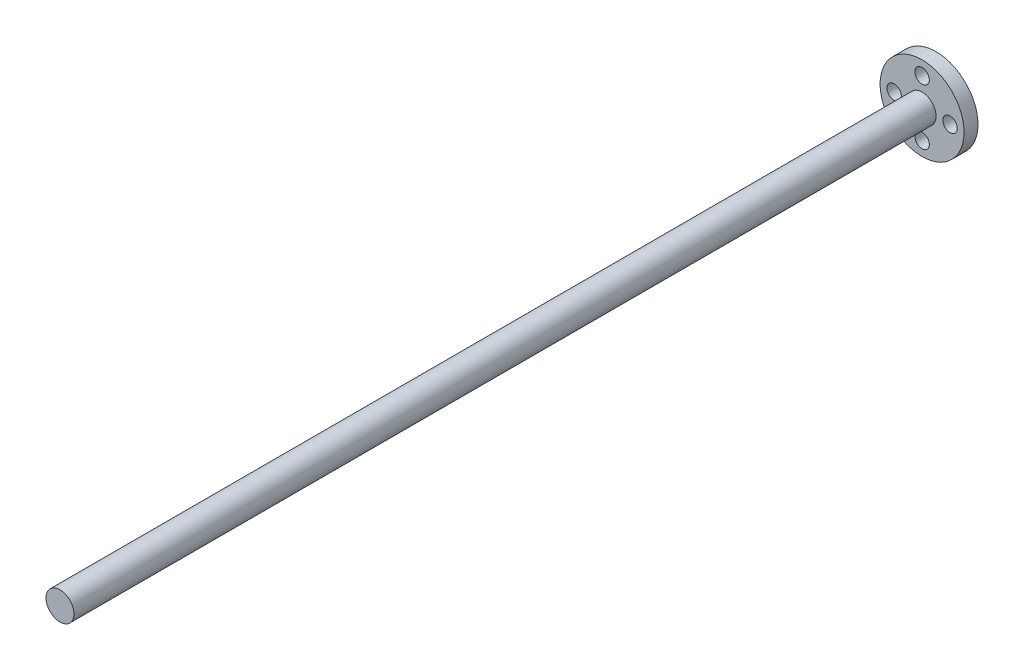
SolidWorks part; units mm, degrees
ref_plane "Front Plane" through (0, 0, 0) normal (0, 0, 1) x (1, 0, 0)
ref_plane "Top Plane" through (0, 0, 0) normal (0, 1, 0) x (1, 0, 0)
ref_plane "Right Plane" through (0, 0, 0) normal (1, 0, 0) x (0, 0, -1)
sketch "Sketch1" plane through (0, 0, 0) normal (0, 0, 1) x (1, 0, 0)
  circle A0 centre (0, 0) radius 9
  circle A1 centre (0, 0) radius 6 construction
  circle A2 centre (-6, 0) radius 1.55
  circle A3 centre (0, 6) radius 1.55
  circle A4 centre (6, 0) radius 1.55
  circle A5 centre (0, -6) radius 1.55
  point P15 (0, 0)
  dimension "D1" = 4
extrude "Boss-Extrude1" add sketch "Sketch1" along normal blind 3
sketch "Sketch2" plane through (0, 0, 3) normal (0, 0, 1) x (1, 0, 0)
  circle A0 centre (0, 0) radius 3
extrude "Boss-Extrude2" add sketch "Sketch2" along normal blind 185
